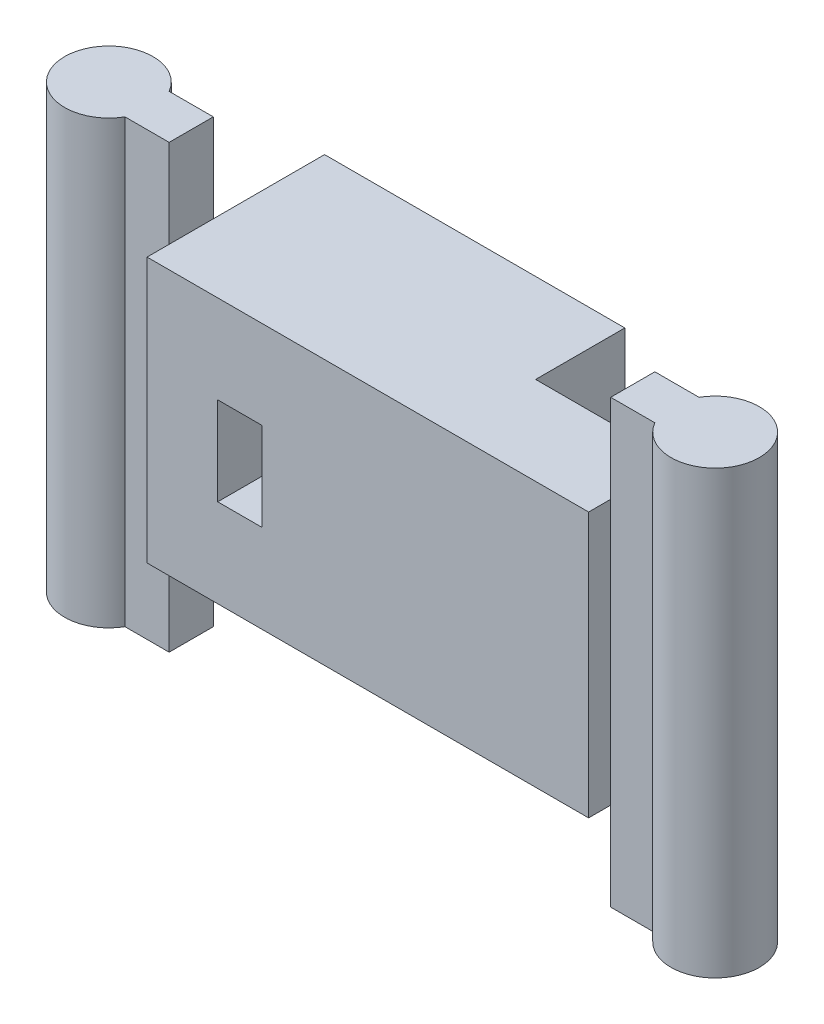
SolidWorks part; units mm, degrees
ref_plane "Plano frontal" through (0, 0, 0) normal (0, 0, 1) x (1, 0, 0)
ref_plane "Plano superior" through (0, 0, 0) normal (0, 1, 0) x (1, 0, 0)
ref_plane "Plano direito" through (0, 0, 0) normal (1, 0, 0) x (0, 0, -1)
sketch "Esboço1" plane through (0, 0, 0) normal (0, 0, 1) x (1, 0, 0)
  line L0 (0, 0) -> (-6.5, 0) construction
  line L1 (-17, -15) -> (17, -15)
  line L2 (-17, -15) -> (-17, 15)
  line L3 (-17, 15) -> (17, 15)
  line L4 (17, -15) -> (17, 15)
  line L5 (-17, -15) -> (17, 15) construction
  line L6 (-17, 15) -> (17, -15) construction
  line L7 (-4, -5) -> (-9, -5)
  line L8 (-4, -5) -> (-4, 5)
  line L9 (-4, 5) -> (-9, 5)
  line L10 (-9, -5) -> (-9, 5)
  line L11 (-4, -5) -> (-9, 5) construction
  line L12 (-4, 5) -> (-9, -5) construction
  line L13 (-6.5, 0) -> (-17, 0) construction
  point P0 (0, 0)
  point P6 (-6.5, 0)
  dimension "D1" = 30
  dimension "D2" = 34
  dimension "D3" = 5
  dimension "D4" = 8
  dimension "D5" = 10
extrude "Ressalto-extrusão1" add sketch "Esboço1" along normal blind 20.1
sketch "Esboço2" plane through (17, 0, 0) normal (1, 0, 0) x (0, 0, -1)
  line L0 (-20.1, -15) -> (0, -15) construction
  line L1 (-20.1, 15) -> (-10.1, 15)
  line L2 (-20.1, 15) -> (-20.1, -15)
  line L3 (-20.1, -15) -> (-10.1, -15)
  line L4 (-10.1, 15) -> (-10.1, -15)
  dimension "D1" = 10
extrude "Ressalto-extrusão2" add sketch "Esboço2" along normal blind 16
ref_plane "Plano1" through (0, 25, 0) normal (0, 1, 0) x (1, 0, 0)
sketch "Esboço3" plane through (0, 25, 0) normal (0, 1, 0) x (1, 0, 0)
  line L0 (42.3301, -15.1) -> (33, -15.1) construction
  line L1 (33, -10.1) -> (33, -20.1) construction
  line L2 (33, -12.6) -> (38, -12.6)
  line L3 (33, -17.6) -> (38, -17.6)
  line L4 (33, -10.1) -> (17, -10.1) construction
  line L5 (33, -20.1) -> (-17, -20.1) construction
  line L6 (33, -12.6) -> (33, -17.6)
  line L7 (8, -20.1) -> (8, 0) construction
  line L8 (17, 0) -> (-17, 0) construction
  line L9 (-26.3301, -15.1) -> (-17, -15.1) construction
  line L10 (-17, -12.6) -> (-17, -17.6)
  line L11 (-17, -17.6) -> (-22, -17.6)
  line L12 (-17, -12.6) -> (-22, -12.6)
  arc A0 (38, -17.6) -> (38, -12.6) centre (42.3301, -15.1) ccw
  arc A1 (-22, -17.6) -> (-22, -12.6) centre (-26.3301, -15.1) cw
  dimension "D4" = 10
  dimension "D1" = 2.5
  dimension "D2" = 2.5
  dimension "D3" = 5
extrude "Ressalto-extrusão3" add sketch "Esboço3" against normal blind 50
